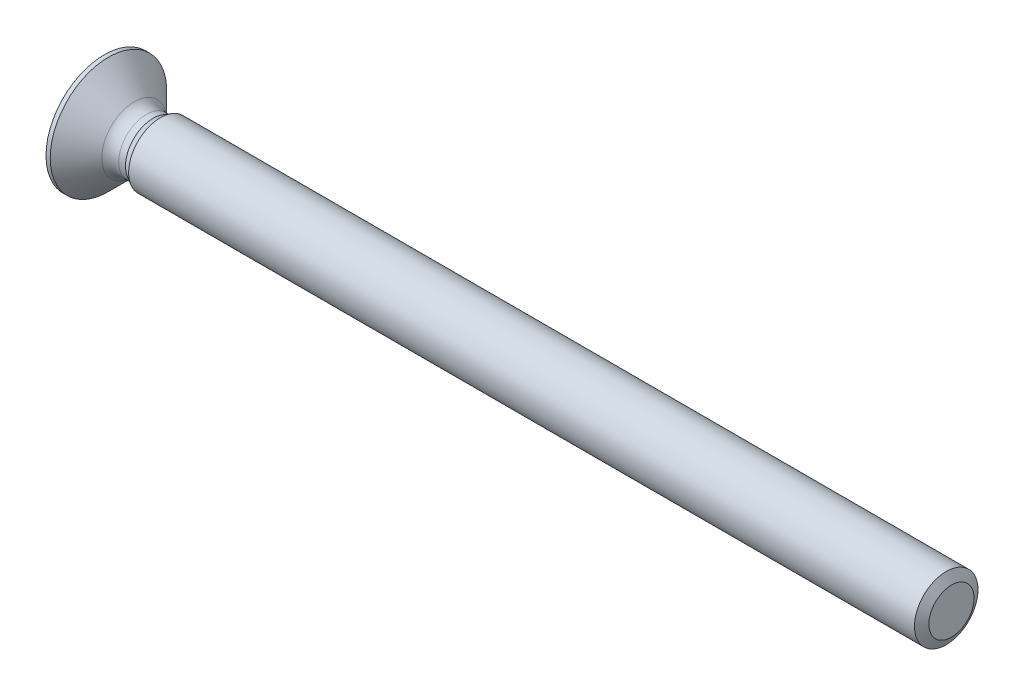
SolidWorks part; units mm, degrees
revolve "基体-旋转" add sketch "草图1" angle 360 about L0
sketch "草图1" plane through (0, 0, 0) normal (0, 0, 1) x (1, 0, 0)
  line L0 (0, 0) -> (4.4175, 0) construction
  line L1 (0, 0) -> (0, 2.75)
  line L2 (0, 2.75) -> (0.199, 2.75)
  line L3 (0.199, 2.75) -> (1.4157, 1.5333)
  line L4 (1.9814, 1.299) -> (2.3019, 1.299)
  line L5 (2.3019, 1.299) -> (2.65, 1.5)
  line L6 (2.65, 1.5) -> (40, 1.5)
  line L7 (40, 1.5) -> (40, 0)
  line L8 (0, 0) -> (40, 0)
  arc A0 (1.9814, 1.299) -> (1.4157, 1.5333) centre (1.9814, 2.099) cw
  point P12 (1.65, 1.299)
  dimension "D2" = 0.8
  dimension "D1" = 2.598
  dimension "d" = 3
  dimension "dk" = 5.5
  dimension "k" = 1.65
  dimension "D5" = 45
  dimension "a" = 1
  dimension "l" = 40
  dimension "D8" = 30
cosmetic thread "装饰螺纹线2" parameters "D1"=37.35, "D2"=2.5
ref_plane "前视" through (0, 0, 0) normal (0, 0, 1) x (1, 0, 0)
ref_plane "上视" through (0, 0, 0) normal (0, 1, 0) x (1, 0, 0)
ref_plane "右视" through (0, 0, 0) normal (1, 0, 0) x (0, 0, -1)
sketch "尺寸草图" plane through (0, 0, 0) normal (0, 0, 1) x (1, 0, 0)
  line L0 (0, 0) -> (40, 0)
  point P3 (1.65, 0)
  point P4 (1, 0)
  point P5 (3, 0)
  point P6 (5.5, 0)
  point P7 (36.8, 0)
  point P8 (3.5943, 0)
  point P9 (39.2, 0)
  point P10 (37.9, 0)
  point P11 (39.5, 0)
  dimension "d" = 3
  dimension "dk" = 5.5
  dimension "k" = 1.65
  dimension "a" = 1
  dimension "l" = 40
  dimension "r" = 0.8
  dimension "m" = 3.2
  dimension "h" = 2.1
  dimension "p" = 0.5
sketch "草图2" plane through (0, 0, 0) normal (0, 0, 1) x (1, 0, 0)
  line L0 (39.7527, 1.5) -> (40.2527, 1.5)
  line L1 (40.2527, 1.5) -> (40, 1.067)
  line L2 (40, 1.067) -> (39.7527, 1.5)
  line L3 (40, -1.5) -> (40, 1.5) construction
  line L6 (0, 0) -> (-0.4315, 0) construction
  dimension "D1" = 0.5
  dimension "D2" = 0.433
  dimension "D3" = 1.5
  dimension "D4" = 60
revolve "切除-旋转1" cut sketch "草图2" angle 360 about L6
pattern_linear "阵列(线性)1" [suppressed] count 75 spacing 0.5 along (1, 0, 0)
sketch "草图3" plane through (0, 0, 0) normal (-1, 0, 0) x (0, 0, 1)
  line L0 (0, 0) -> (1.6329, 0) construction
  line L1 (0, 0) -> (0, 0.8499) construction
  line L2 (-1.6, 0.25) -> (1.6, 0.25)
  line L3 (-1.6, 0.25) -> (-1.6, -0.25)
  line L4 (-1.6, -0.25) -> (1.6, -0.25)
  line L5 (1.6, 0.25) -> (1.6, -0.25)
  dimension "m" = 3.2
  dimension "D1" = 0.5
ref_plane "基准面1" through (2.1, 0, 0) normal (-1, 0, 0) x (0, 0, 1)
sketch "草图4" plane through (2.1, 0, 0) normal (-1, 0, 0) x (0, 0, 1)
  point P0 (0, 0)
loft "切除-放样1" cut profiles "草图3", "草图4"
pattern_circular "阵列(圆周)1" count 2 every 90 about axis through (0, 0, 0) along (1, 0, 0) of "切除-放样1"
equation "\"l@草图1\" = \"l@尺寸草图\""
equation "\"k@草图1\" = \"k@尺寸草图\""
equation "\"a@草图1\" = \"a@尺寸草图\""
equation "\"d@草图1\" = \"d@尺寸草图\""
equation "\"dk@草图1\" = \"dk@尺寸草图\""
equation "\"D2@草图1\" = \"r@尺寸草图\""
equation "\"m@草图3\" = \"m@尺寸草图\""
equation "\"h@基准面1\" = \"h@尺寸草图\""
equation "\"D3@阵列(线性)1\" = \"p@尺寸草图\""
equation "\"D3@草图2\" = \"d@草图1\" / 2"
equation "\"D1@装饰螺纹线2\" = \"l@草图1\" - \"k@草图1\" - \"a@草图1\""
equation "\"D2@装饰螺纹线2\" = \"d@尺寸草图\"- \"p@尺寸草图\""
equation "\"D1@阵列(线性)1\" = (  \"l@草图1\" - \"k@草图1\" - \"a@草图1\" )  / \"p@尺寸草图\""
equation "\"D1@草图3\" = \"p@尺寸草图\""
equation "\"D1@草图1\" = \"d@尺寸草图\"*0.866"
equation "\"D2@草图2\" = \"p@尺寸草图\"*0.866"
equation "\"D1@草图2\" = \"p@尺寸草图\""
